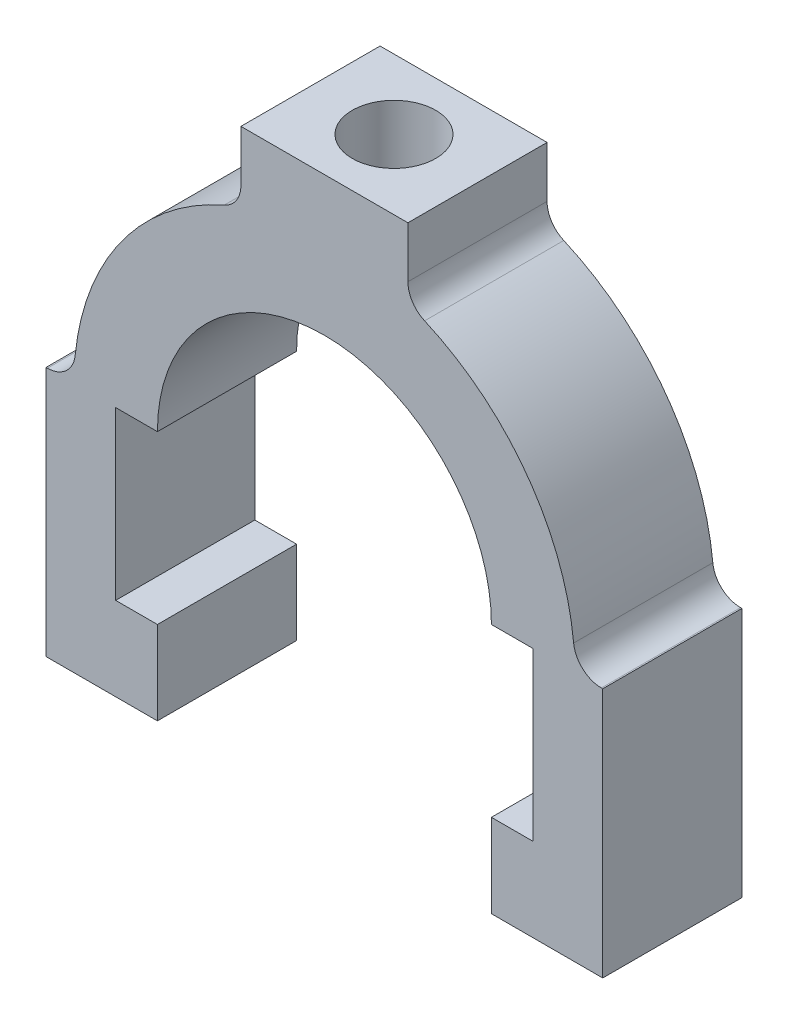
SolidWorks part; units mm, degrees
ref_plane "정면" through (0, 0, 0) normal (0, 0, 1) x (1, 0, 0)
ref_plane "윗면" through (0, 0, 0) normal (0, 1, 0) x (1, 0, 0)
ref_plane "우측면" through (0, 0, 0) normal (1, 0, 0) x (0, 0, -1)
sketch "스케치1" plane through (0, 0, 0) normal (0, 0, 1) x (1, 0, 0)
  line L0 (0, 0) -> (0, 80) construction
  line L1 (-12, 80) -> (12, 80)
  line L2 (12, 80) -> (12, 69.9411)
  line L3 (24, 36) -> (30, 36)
  line L4 (40, 36) -> (40, 0)
  line L5 (30, 36) -> (30, 12)
  line L6 (36, 36) -> (40, 36)
  line L7 (30, 12) -> (24, 12)
  line L8 (24, 12) -> (24, 0)
  line L9 (24, 0) -> (40, 0)
  line L10 (-24, 0) -> (-40, 0)
  line L11 (-24, 12) -> (-24, 0)
  line L12 (-30, 12) -> (-24, 12)
  line L13 (-36, 36) -> (-40, 36)
  line L14 (-30, 36) -> (-30, 12)
  line L15 (-40, 36) -> (-40, 0)
  line L16 (-24, 36) -> (-30, 36)
  line L17 (-12, 80) -> (-12, 69.9411)
  arc A1 (24, 36) -> (-24, 36) centre (0, 36) ccw
  arc A2 (36, 36) -> (12, 69.9411) centre (0, 36) ccw
  arc A3 (-36, 36) -> (-12, 69.9411) centre (0, 36) cw
  point P24 (0, 0)
  point P25 (0, 0)
  point P26 (0, 0)
  point P27 (0, 0)
  point P28 (0, 0)
  point P29 (40, -0.1015)
  point P30 (40, 3.3674)
  point P31 (0, 0)
  point P32 (24, -3.5704)
  point P33 (0, 0)
  dimension "D2" = 36
  dimension "D4" = 24
  dimension "D1" = 80
  dimension "D3" = 36
  dimension "D5" = 24
  dimension "D6" = 80
  dimension "D7" = 10
  dimension "D8" = 16
  dimension "D9" = 12
extrude "보스-돌출3" add sketch "스케치1" along normal mid plane 20
sketch "스케치3" plane through (0, 80, 0) normal (0, 1, 0) x (1, 0, 0)
  circle A0 centre (0, 0) radius 6
  dimension "D1" = 12
extrude "컷-돌출1" cut sketch "스케치3" against normal through all
fillet "필렛1" radius 4 4 edges at (-36, 36, 0) (-12, 69.9411, 0) (36, 36, 0) (12, 69.9411, 0)
